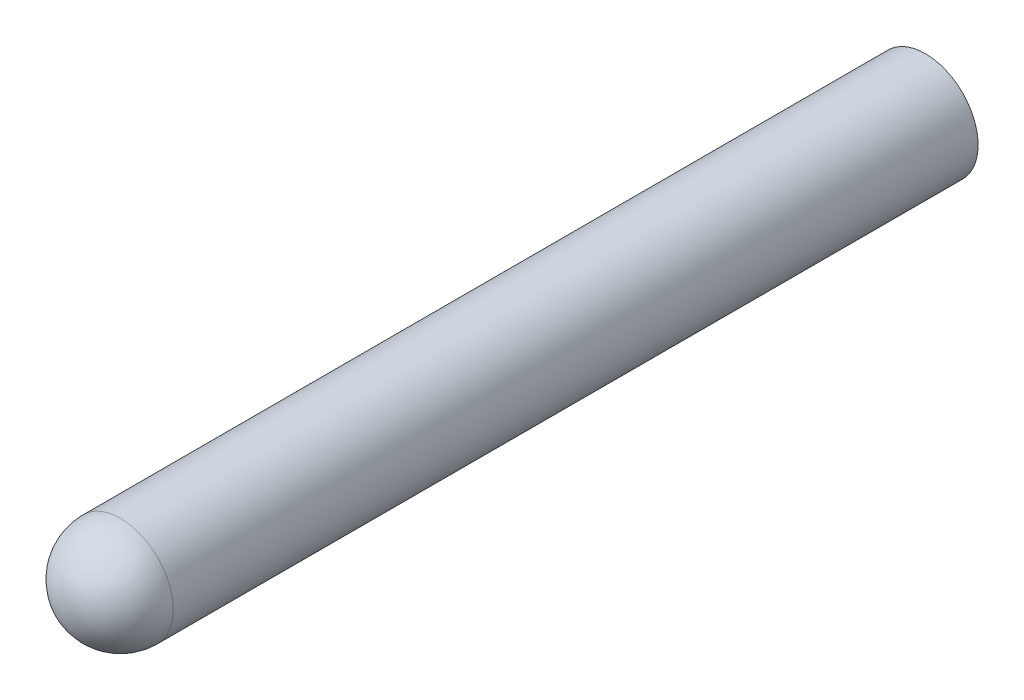
SolidWorks part; units mm, degrees
ref_plane "Alzado" through (0, 0, 0) normal (0, 0, 1) x (1, 0, 0)
ref_plane "Planta" through (0, 0, 0) normal (0, 1, 0) x (1, 0, 0)
ref_plane "Vista lateral" through (0, 0, 0) normal (1, 0, 0) x (0, 0, -1)
sketch "Croquis1" plane through (0, 0, 0) normal (0, 1, 0) x (1, 0, 0)
  line L0 (0, -25.15) -> (0, -24.3)
  line L1 (6.15, -19) -> (6.15, 74.85)
  line L2 (6.15, 74.85) -> (5.3, 74.85)
  line L3 (5.3, 74.85) -> (5.3, -19)
  line L4 (0, -25.4498) -> (0, 174.5502) construction
  arc A1 (0, -24.3) -> (5.3, -19) centre (0, -19) ccw
  arc A2 (0, -25.15) -> (6.15, -19) centre (0, -19) ccw
  dimension "D1" = 100
revolve "Revolución1" add sketch "Croquis1" angle 360 about L4
